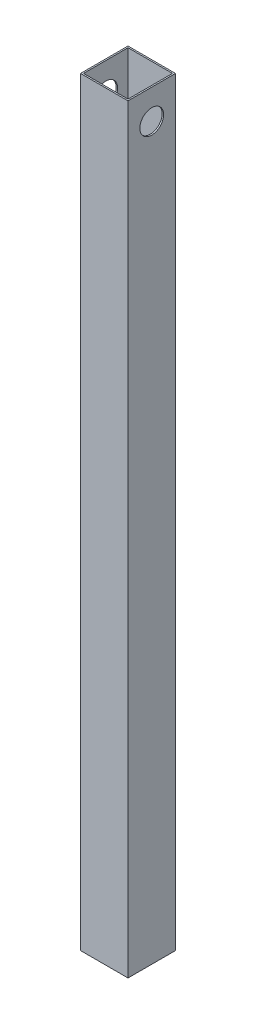
SolidWorks part; units mm, degrees
material "6061-T6 (SS)"
ref_plane "Front Plane" through (0, 0, 0) normal (0, 0, 1) x (1, 0, 0)
ref_plane "Top Plane" through (0, 0, 0) normal (0, 1, 0) x (1, 0, 0)
ref_plane "Right Plane" through (0, 0, 0) normal (1, 0, 0) x (0, 0, -1)
sketch "Sketch1" plane through (0, 0, 0) normal (0, 1, 0) x (1, 0, 0)
  line L1 (0, 0) -> (50.8, 0)
  line L2 (0, 0) -> (0, 50.8)
  line L3 (0, 50.8) -> (50.8, 50.8)
  line L4 (50.8, 0) -> (50.8, 50.8)
  dimension "D1" = 50.8
extrude "Boss-Extrude1" add sketch "Sketch1" along normal mid plane 812.8
shell "Shell1" thickness 1.5875
sketch "Sketch2" plane through (50.8, 0, 0) normal (1, 0, 0) x (0, 0, -1)
  line L0 (0, 406.4) -> (0, -406.4) construction
  line L1 (0, 406.4) -> (50.8, 406.4) construction
  circle A0 centre (25.4, 374.65) radius 12.7
  dimension "D1" = 25.4
  dimension "D2" = 25.4
  dimension "D3" = 31.75
extrude "Cut-Extrude1" cut sketch "Sketch2" against normal through all
